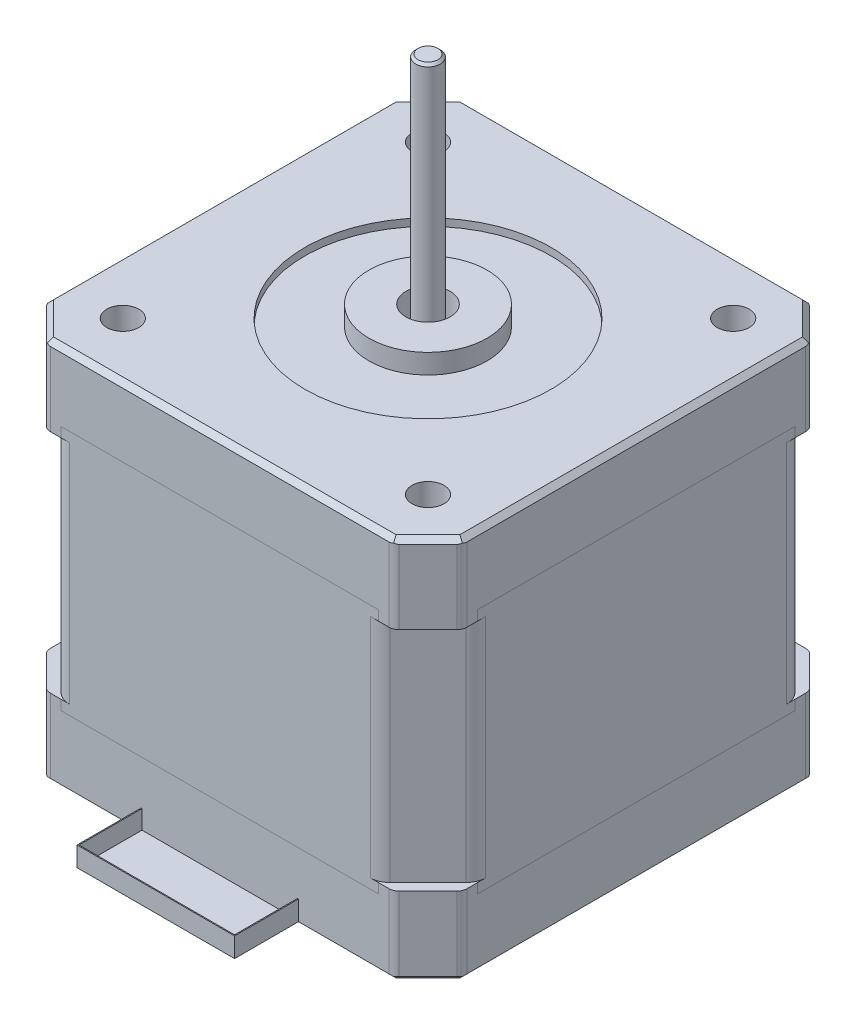
SolidWorks part; units mm, degrees
ref_plane "Front Plane" through (0, 0, 0) normal (0, 0, 1) x (1, 0, 0)
ref_plane "Top Plane" through (0, 0, 0) normal (0, 1, 0) x (1, 0, 0)
ref_plane "Right Plane" through (0, 0, 0) normal (1, 0, 0) x (0, 0, -1)
sketch "Sketch1" plane through (0, 0, 0) normal (0, 1, 0) x (1, 0, 0)
  line L0 (-41.2413, 0) -> (21.15, 0) construction
  line L1 (0, -27.9894) -> (0, 21.15) construction
  line L2 (-21.15, -17.6145) -> (-21.15, 17.6145)
  line L3 (-21.15, 17.6145) -> (-17.6145, 21.15)
  line L4 (-17.6145, 21.15) -> (17.6145, 21.15)
  line L5 (17.6145, 21.15) -> (21.15, 17.6145)
  line L6 (21.15, 17.6145) -> (21.15, -17.6145)
  line L7 (21.15, -17.6145) -> (17.6145, -21.15)
  line L8 (17.6145, -21.15) -> (-17.6145, -21.15)
  line L9 (-17.6145, -21.15) -> (-21.15, -17.6145)
  dimension "D1" = 42.3
  dimension "D2" = 45
  dimension "D3" = 5
extrude "Boss-Extrude1" add sketch "Sketch1" against normal blind 8
sketch "Sketch2" plane through (0, 0, 0) normal (0, 1, 0) x (1, 0, 0)
  line L0 (-21.15, 0) -> (21.15, 0) construction
  line L1 (-21.15, 17.6145) -> (-21.15, -17.6145) construction
  line L2 (21.15, -17.6145) -> (21.15, 17.6145) construction
  line L3 (0, -21.15) -> (0, 21.15) construction
  line L4 (-17.6145, -21.15) -> (17.6145, -21.15) construction
  line L5 (17.6145, 21.15) -> (-17.6145, 21.15) construction
  circle A0 centre (-15.5, 15.5) radius 1.6248
  circle A1 centre (15.5, 15.5) radius 1.6248
  circle A2 centre (15.5, -15.5) radius 1.6248
  circle A3 centre (-15.5, -15.5) radius 1.6248
  dimension "D1" = 31
  dimension "D2" = 31
extrude "Cut-Extrude1" cut sketch "Sketch2" against normal blind 6
chamfer "Chamfer1" distance 0.5 angle 45 8 edges at (-21.15, 0, 0) (-19.3822, 0, -19.3822) (0, 0, -21.15) (19.3822, 0, -19.3822) (21.15, 0, 0) (19.3822, 0, 19.3822) (0, 0, 21.15) (-19.3822, 0, 19.3822)
sketch "Sketch3" plane through (21.15, 0, 0) normal (1, 0, 0) x (0, 0, -1)
  line L0 (-16.1145, -8) -> (16.1145, -8)
  line L1 (-17.6145, -8) -> (17.6145, -8) construction
  line L2 (-16.1145, -8) -> (-16.1145, -7)
  line L3 (-16.1145, -7) -> (16.1145, -7)
  line L4 (16.1145, -7) -> (16.1145, -8)
  dimension "D1" = 1.5
  dimension "D2" = 1.5
  dimension "D3" = 1
extrude "Cut-Extrude2" cut sketch "Sketch3" against normal through all
sketch "Sketch4" plane through (0, 0, 21.15) normal (0, 0, 1) x (1, 0, 0)
  line L0 (-16.1145, -8) -> (-16.1145, -7)
  line L1 (-17.6145, -8) -> (17.6145, -8) construction
  line L2 (-16.1145, -7) -> (16.1145, -7)
  line L3 (16.1145, -7) -> (16.1145, -8)
  line L4 (16.1145, -8) -> (-16.1145, -8)
  line L5 (-17.6145, -8) -> (-17.6145, -0.5) construction
  line L6 (17.6145, -8) -> (17.6145, -0.5) construction
  dimension "D1" = 1.5
  dimension "D2" = 1.5
  dimension "D3" = 1
extrude "Cut-Extrude3" cut sketch "Sketch4" against normal through all
sketch "Sketch5" plane through (0, -8, 0) normal (0, -1, 0) x (1, 0, 0)
  line L0 (-21.15, 16.1145) -> (-16.1145, 21.15)
  line L4 (-21.15, 16.1145) -> (-16.1145, 16.1145)
  line L5 (-16.1145, 16.1145) -> (-16.1145, 21.15)
extrude "Cut-Extrude4" cut sketch "Sketch5" against normal blind 1
mirror "Mirror1" about plane through (0, 0, 0) normal (1, 0, 0) of "Cut-Extrude4"
mirror "Mirror2" about plane through (0, 0, 0) normal (0, 0, 1) of "Mirror1", "Cut-Extrude4"
sketch "Sketch6" plane through (0, -7, 0) normal (0, -1, 0) x (1, 0, 0)
  line L0 (-21.15, -16.1145) -> (-21.15, 16.1145)
  line L1 (-21.15, 16.1145) -> (-16.1145, 21.15)
  line L2 (-16.1145, 21.15) -> (16.1145, 21.15)
  line L3 (16.1145, 21.15) -> (21.15, 16.1145)
  line L4 (21.15, 16.1145) -> (21.15, -16.1145)
  line L5 (21.15, -16.1145) -> (16.1145, -21.15)
  line L6 (16.1145, -21.15) -> (-16.1145, -21.15)
  line L7 (-16.1145, -21.15) -> (-21.15, -16.1145)
extrude "Boss-Extrude2" add sketch "Sketch6" along normal blind 24
sketch "Sketch12" plane through (21.15, 0, 0) normal (1, 0, 0) x (0, 0, -1)
  line L0 (-16.1145, -8) -> (-16.1145, -7)
  line L1 (-16.1145, -7) -> (16.1145, -7)
  line L2 (16.1145, -7) -> (16.1145, -8)
  dimension "D1" = 1
split line "Split Line5"
sketch "Sketch13" plane through (0, 0, -21.15) normal (0, 0, -1) x (-1, 0, 0)
  line L0 (-16.1145, -8) -> (-16.1145, -7)
  line L1 (-16.1145, -7) -> (16.1145, -7)
  line L2 (16.1145, -7) -> (16.1145, -8)
  dimension "D1" = 1
split line "Split Line6"
sketch "Sketch14" plane through (-21.15, 0, 0) normal (-1, 0, 0) x (0, 0, 1)
  line L0 (-16.1145, -8) -> (-16.1145, -7)
  line L1 (-16.1145, -7) -> (16.1145, -7)
  line L2 (16.1145, -7) -> (16.1145, -8)
  dimension "D1" = 1
split line "Split Line7"
sketch "Sketch15" plane through (0, 0, 21.15) normal (0, 0, 1) x (1, 0, 0)
  line L0 (-16.1145, -8) -> (-16.1145, -7)
  line L1 (-16.1145, -7) -> (16.1145, -7)
  line L2 (16.1145, -7) -> (16.1145, -8)
  dimension "D1" = 1
split line "Split Line8"
sketch "Sketch16" plane through (0, -31, 0) normal (0, -1, 0) x (1, 0, 0)
  line L0 (-21.15, -17.6145) -> (-21.15, 17.6145)
  line L1 (-21.15, 17.6145) -> (-17.6145, 21.15)
  line L2 (-17.6145, 21.15) -> (17.6145, 21.15)
  line L3 (17.6145, 21.15) -> (21.15, 17.6145)
  line L4 (21.15, 17.6145) -> (21.15, -17.6145)
  line L5 (21.15, -17.6145) -> (17.6145, -21.15)
  line L6 (17.6145, -21.15) -> (-17.6145, -21.15)
  line L7 (-17.6145, -21.15) -> (-21.15, -17.6145)
extrude "Boss-Extrude4" add sketch "Sketch16" along normal blind 8
sketch "Sketch17" plane through (0, 0, 21.15) normal (0, 0, 1) x (1, 0, 0)
  line L0 (-16.1145, -31) -> (-16.1145, -32)
  line L1 (-16.1145, -32) -> (16.1145, -32)
  line L2 (16.1145, -32) -> (16.1145, -31)
  dimension "D1" = 1
split line "Split Line9"
sketch "Sketch18" plane through (21.15, 0, 0) normal (1, 0, 0) x (0, 0, -1)
  line L0 (-16.1145, -31) -> (-16.1145, -32)
  line L1 (-16.1145, -32) -> (16.1145, -32)
  line L2 (16.1145, -32) -> (16.1145, -31)
  dimension "D1" = 1
split line "Split Line10"
sketch "Sketch19" plane through (0, 0, -21.15) normal (0, 0, -1) x (-1, 0, 0)
  line L0 (-16.1145, -31) -> (-16.1145, -32)
  line L1 (-16.1145, -32) -> (16.1145, -32)
  line L2 (16.1145, -32) -> (16.1145, -31)
  dimension "D1" = 1
split line "Split Line11"
sketch "Sketch20" plane through (-21.15, 0, 0) normal (-1, 0, 0) x (0, 0, 1)
  line L0 (-16.1145, -31) -> (-16.1145, -32)
  line L1 (-16.1145, -32) -> (16.1145, -32)
  line L2 (16.1145, -32) -> (16.1145, -31)
  dimension "D1" = 1
split line "Split Line12"
sketch "Sketch22" plane through (0, 0, 21.15) normal (0, 0, 1) x (1, 0, 0)
  line L0 (-8, -39) -> (8, -39)
  line L1 (17.6145, -39) -> (-17.6145, -39) construction
  line L2 (8, -39) -> (8, -36.5)
  line L3 (8, -36.5) -> (-8, -36.5)
  line L4 (-8, -36.5) -> (-8, -39)
  line L5 (0, 0) -> (0, -39) construction
  dimension "D1" = 16
  dimension "D2" = 2.5
extrude "Boss-Extrude5" add sketch "Sketch22" along normal blind 6.5
chamfer "Chamfer3" distance 0.5 angle 45 12 edges at (-21.15, -39, 0) (-19.3822, -39, 19.3822) (-12.8072, -39, 21.15) (-8, -39, 24.4) (0, -39, 27.65) (8, -39, 24.4) (12.8072, -39, 21.15) (19.3822, -39, 19.3822) (21.15, -39, 0) (19.3822, -39, -19.3822) (0, -39, -21.15) (-19.3822, -39, -19.3822)
sketch "Sketch23" plane through (0, -36.5, 0) normal (0, 1, 0) x (1, 0, 0)
  line L0 (-8, -27.65) -> (-8, -21.15) construction
  line L1 (-7.9, -21.15) -> (7.9, -21.15)
  line L2 (-7.9, -21.15) -> (-7.9, -27.55)
  line L3 (-7.9, -27.55) -> (7.9, -27.55)
  line L4 (7.9, -21.15) -> (7.9, -27.55)
  line L5 (-7.9, -21.15) -> (7.9, -27.55) construction
  line L6 (-7.9, -27.55) -> (7.9, -21.15) construction
  line L7 (8, -27.65) -> (8, -21.15) construction
  line L8 (8, -27.65) -> (-8, -27.65) construction
  line L10 (8, -21.15) -> (-8, -21.15) construction
  point P0 (0, -24.35)
  dimension "D1" = 0.1
  dimension "D2" = 0.1
  dimension "D3" = 0.1
extrude "Cut-Extrude5" cut sketch "Sketch23" against normal blind 1.9
sketch "Sketch24" plane through (0, 0, 0) normal (0, 1, 0) x (1, 0, 0)
  circle A0 centre (0, 0) radius 12.5
  dimension "D1" = 25
extrude "Cut-Extrude6" cut sketch "Sketch24" against normal blind 0.75
sketch "Sketch25" plane through (0, -0.75, 0) normal (0, 1, 0) x (1, 0, 0)
  circle A0 centre (0, 0) radius 6
  dimension "D1" = 12
extrude "Boss-Extrude6" add sketch "Sketch25" along normal blind 2
sketch "Sketch26" plane through (0, 1.25, 0) normal (0, 1, 0) x (1, 0, 0)
  circle A0 centre (0, 0) radius 2.25
  dimension "D1" = 4.5
extrude "Cut-Extrude7" cut sketch "Sketch26" against normal blind 5
sketch "Sketch27" plane through (0, -3.75, 0) normal (0, 1, 0) x (1, 0, 0)
  circle A0 centre (0, 0) radius 1.2521
  dimension "D1" = 2.5041
extrude "Boss-Extrude7" add sketch "Sketch27" along normal blind 27
chamfer "Chamfer5" distance 0.25 angle 45 1 edges at (0, 23.25, 1.2521)
fillet "Fillet1" radius 2 8 edges at (-16.1145, -19.5, 21.15) (-21.15, -19.5, 16.1145) (-21.15, -19.5, -16.1145) (-16.1145, -19.5, -21.15) (21.15, -19.5, -16.1145) (16.1145, -19.5, -21.15) (21.15, -19.5, 16.1145) (16.1145, -19.5, 21.15)
fillet "Fillet3" radius 1 8 edges at (-17.6145, -4.25, 21.15) (-21.15, -4.25, 17.6145) (-21.15, -4.25, -17.6145) (-17.6145, -4.25, -21.15) (17.6145, -4.25, -21.15) (21.15, -4.25, -17.6145) (17.6145, -4.25, 21.15) (21.15, -4.25, 17.6145)
fillet "Fillet4" radius 1 8 edges at (-17.6145, -34.75, 21.15) (-21.15, -34.75, 17.6145) (-21.15, -34.75, -17.6145) (-17.6145, -34.75, -21.15) (17.6145, -34.75, -21.15) (21.15, -34.75, -17.6145) (21.15, -34.75, 17.6145) (17.6145, -34.75, 21.15)
